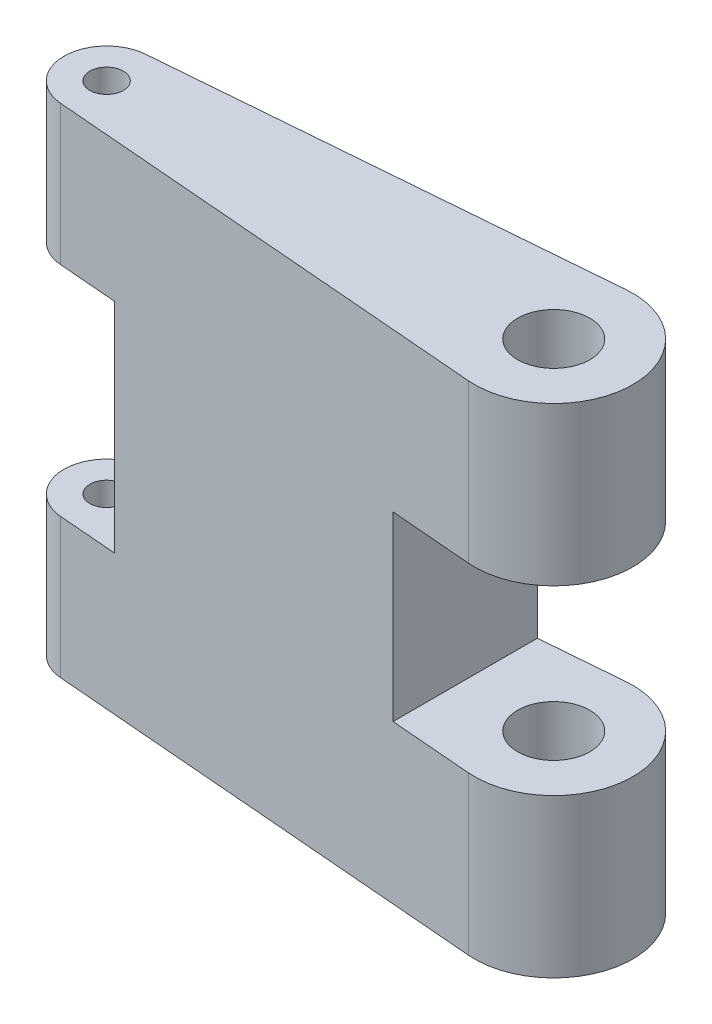
SolidWorks part; units mm, degrees
ref_plane "Front Plane" through (0, 0, 0) normal (0, 0, 1) x (1, 0, 0)
ref_plane "Top Plane" through (0, 0, 0) normal (0, 1, 0) x (1, 0, 0)
ref_plane "Right Plane" through (0, 0, 0) normal (1, 0, 0) x (0, 0, -1)
sketch "Sketch2" plane through (0.0086, 0, 0) normal (0, 1, 0) x (1, 0, 0)
  line L0 (-0.3022, 3.5847) -> (-20.4868, 1.9314)
  line L1 (-20.4868, -1.9314) -> (-0.3022, -3.5847)
  line L2 (-0.0086, 0) -> (-20.3286, 0) construction
  arc A0 (-20.4868, 1.9314) -> (-20.4868, -1.9314) centre (-20.3286, 0) ccw
  arc A1 (-0.3022, -3.5847) -> (-0.3022, 3.5847) centre (-0.0086, 0) ccw
  dimension "D2" = 1.9379
  dimension "D3" = 3.5967
  dimension "D1" = 20.32
extrude "Extrude2" add sketch "Sketch2" against normal mid plane 22.6082 separate body
sketch "Sketch4" plane through (0, 0, 0) normal (0, 0, 1) x (1, 0, 0)
  line L0 (-4.0233, 0) -> (3.5967, 0) construction
  line L1 (-4.0233, -4.1262) -> (3.5967, -4.1262)
  line L2 (-4.0233, -4.1262) -> (-4.0233, 4.1262)
  line L3 (-4.0233, 4.1262) -> (3.5967, 4.1262)
  line L4 (3.5967, -4.1262) -> (3.5967, 4.1262)
  line L5 (3.5967, -11.3041) -> (3.5967, 11.3041) construction
  line L6 (-0.2936, -11.3041) -> (3.5967, -11.3041) construction
  dimension "D1" = 7.62
  dimension "D2" = 7.1779
extrude "Cut-Extrude5" cut sketch "Sketch4" against normal through all and the other way through all
sketch "Sketch5" plane through (0, -11.3041, 0) normal (0, -1, 0) x (1, 0, 0)
  circle A0 centre (0, 0) radius 1.64
  dimension "D1" = 3.28
extrude "Cut-Extrude6" cut sketch "Sketch5" against normal through all
sketch "Sketch6" plane through (0, 0, 0) normal (0, 0, 1) x (1, 0, 0)
  line L0 (-20.4782, 11.3041) -> (-0.2936, 11.3041) construction
  line L1 (-22.2579, 4.9541) -> (-17.8129, 4.9541)
  line L2 (-22.2579, 4.9541) -> (-22.2579, -4.9541)
  line L3 (-22.2579, -4.9541) -> (-17.8129, -4.9541)
  line L4 (-17.8129, 4.9541) -> (-17.8129, -4.9541)
  line L5 (-20.4782, -11.3041) -> (-0.2936, -11.3041) construction
  line L6 (-22.2579, 11.3041) -> (-22.2579, -11.3041) construction
  dimension "D1" = 6.35
  dimension "D2" = 6.35
  dimension "D3" = 4.445
  dimension "D4" = 9.9082
extrude "Extrude4" cut sketch "Sketch6" against normal through all and the other way through all
sketch "Sketch7" plane through (0, -11.3041, 0) normal (0, -1, 0) x (1, 0, 0)
  circle A0 centre (-20.32, 0) radius 0.762
extrude "Extrude5" cut sketch "Sketch7" against normal through all
